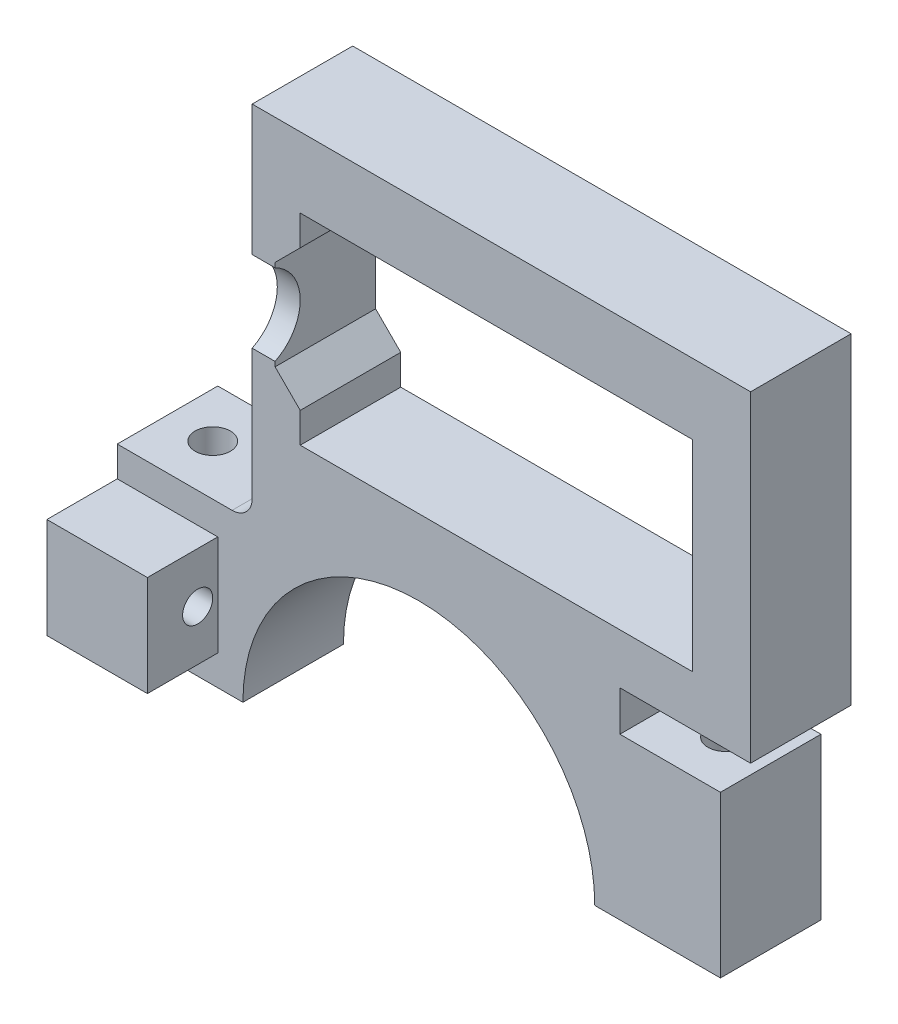
SolidWorks part; units mm, degrees
ref_plane "Ön Düzlem" through (0, 0, 0) normal (0, 0, 1) x (1, 0, 0)
ref_plane "Üst Düzlem" through (0, 0, 0) normal (0, 1, 0) x (1, 0, 0)
ref_plane "Sağ Düzlem" through (0, 0, 0) normal (1, 0, 0) x (0, 0, -1)
sketch "Çizim1" plane through (0, 0, 0) normal (0, 0, 1) x (1, 0, 0)
  line L0 (-30, 0) -> (-17.5, 0)
  line L1 (17.5, 0) -> (30, 0)
  line L4 (-30, 0) -> (-30, 52)
  line L5 (-30, 52) -> (30, 52)
  line L6 (30, 0) -> (30, 52)
  arc A0 (17.5, 0) -> (-17.5, 0) centre (0, 0) ccw
  dimension "D1" = 35
  dimension "D2" = 30
  dimension "D3" = 60
  dimension "D4" = 52
extrude "Yükseklik-Ekstrüzyon1" add sketch "Çizim1" along normal blind 10
sketch "Sketch1" plane through (0, 0, 10) normal (0, 0, 1) x (1, 0, 0)
  line L0 (30, 16) -> (20, 16)
  line L1 (30, 0) -> (30, 52) construction
  line L2 (20, 16) -> (20, 20)
  line L3 (20, 20) -> (30, 20)
  line L4 (30, 52) -> (-30, 52) construction
  line L5 (30, 20) -> (30, 16)
  line L7 (17.5, 0) -> (30, 0) construction
  line L8 (-30, 16) -> (-20, 16)
  line L9 (-30, 52) -> (-30, 0) construction
  line L10 (-20, 16) -> (-20, 52)
  line L11 (-20, 52) -> (-30, 52)
  line L12 (-30, 52) -> (-30, 16)
  dimension "D1" = 4
  dimension "D2" = 16
  dimension "D3" = 10
extrude "Cut-Extrude1" cut sketch "Sketch1" against normal up to next
sketch "Sketch2" plane through (0, 16, 0) normal (0, 1, 0) x (1, 0, 0)
  line L0 (-30, 0) -> (-30, -10) construction
  line L1 (-20, 0) -> (-30, 0) construction
  line L2 (30, 0) -> (30, -10) construction
  circle A0 centre (-25.5, -5) radius 1.75
  circle A1 centre (25.5, -5) radius 1.75
  dimension "D1" = 3.5
  dimension "D2" = 4.5
  dimension "D3" = 5
  dimension "D4" = 4.5
extrude "Cut-Extrude2" cut sketch "Sketch2" against normal up to next
sketch "Sketch3" plane through (0, 0, 10) normal (0, 0, 1) x (1, 0, 0)
  line L0 (-30, 0) -> (-17.5, 0) construction
  line L1 (-30, 3) -> (-20, 3)
  line L2 (-30, 3) -> (-30, 13)
  line L3 (-30, 13) -> (-20, 13)
  line L4 (-20, 3) -> (-20, 13)
  line L5 (-30, 16) -> (-30, 0) construction
  dimension "D1" = 10
  dimension "D2" = 3
extrude "Boss-Extrude1" add sketch "Sketch3" along normal blind 7
sketch "Sketch4" plane through (-30, 0, 0) normal (-1, 0, 0) x (0, 0, 1)
  line L0 (17, 13) -> (10, 13) construction
  line L1 (17, 13) -> (17, 3) construction
  circle A0 centre (12, 8) radius 1.5
  dimension "D1" = 3
  dimension "D2" = 5
  dimension "D3" = 5
extrude "Cut-Extrude3" cut sketch "Sketch4" against normal up to next
sketch "Sketch6" plane through (0, 0, 10) normal (0, 0, 1) x (1, 0, 0)
  line L1 (-20, 52) -> (-16.5793, 52)
  line L2 (-20, 52) -> (-20, 16)
  line L3 (-20, 16) -> (-18.5793, 16)
  line L4 (-16.5793, 52) -> (-16.5793, 18)
  line L5 (27.2, 45) -> (-11.8, 45)
  line L6 (27.2, 45) -> (27.2, 25)
  line L7 (27.2, 25) -> (-11.8, 25)
  line L8 (-11.8, 45) -> (-11.8, 42)
  line L9 (-11.8, 42) -> (-14.3, 39.5)
  line L10 (-14.3, 39.5) -> (-14.3, 30.5)
  line L11 (-14.3, 30.5) -> (-11.8, 28)
  line L12 (-11.8, 28) -> (-11.8, 25)
  line L13 (30, 20) -> (30, 52) construction
  line L14 (30, 52) -> (-20, 52) construction
  line L15 (-30, 16) -> (-20, 16) construction
  arc A0 (-16.5793, 18) -> (-18.5793, 16) centre (-18.5793, 18) cw
  dimension "D1" = 2
  dimension "D2" = 39
  dimension "D3" = 3
  dimension "D4" = 3
  dimension "D5" = 2.5
  dimension "D6" = 2.8
  dimension "D7" = 7
  dimension "D8" = 20
  dimension "D9" = 45
extrude "Cut-Extrude4" cut sketch "Sketch6" against normal up to next
sketch "Sketch7" plane through (-16.5793, 0, 0) normal (-1, 0, 0) x (0, 0, 1)
  line L0 (10, 18) -> (10, 52) construction
  circle A0 centre (12, 35) radius 4.5
  dimension "D2" = 9
  dimension "D1" = 2
extrude "Cut-Extrude5" cut sketch "Sketch7" against normal up to next
sketch "Sketch8" plane through (30, 0, 0) normal (1, 0, 0) x (0, 0, -1)
  line L1 (-10, 52) -> (0, 52)
  line L2 (-10, 52) -> (-10, 20)
  line L3 (-10, 20) -> (0, 20)
  line L4 (0, 52) -> (0, 20)
extrude "Boss-Extrude2" add sketch "Sketch8" along normal blind 3
